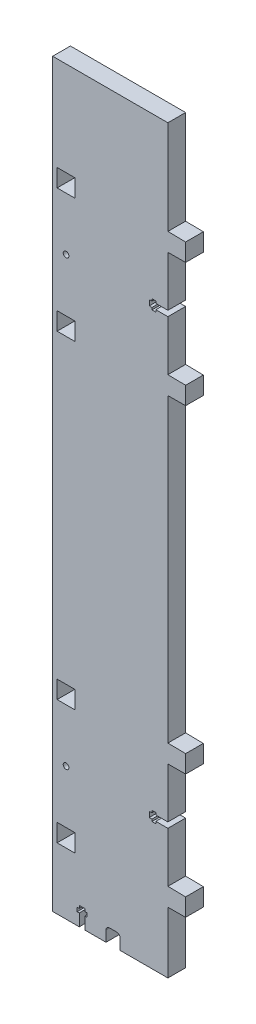
SolidWorks part; units mm, degrees
ref_plane "Front" through (0, 0, 0) normal (0, 0, 1) x (1, 0, 0)
ref_plane "Top" through (0, 0, 0) normal (0, 1, 0) x (1, 0, 0)
ref_plane "Right" through (0, 0, 0) normal (1, 0, 0) x (0, 0, -1)
sketch "Эскиз1" plane through (0, 0, 0) normal (0, 0, 1) x (1, 0, 0)
  line L0 (-37.4993, -208.9512) -> (-37.4993, 208.9512)
  line L1 (-37.4993, 208.9512) -> (27.5007, 208.9512)
  line L2 (-34.9993, 145.8512) -> (-24.8993, 145.8512)
  line L3 (-24.8993, 145.8512) -> (-24.8993, 155.8512)
  line L4 (-24.8993, 155.8512) -> (-34.9993, 155.8512)
  line L5 (-34.9993, 155.8512) -> (-34.9993, 145.8512)
  line L6 (-34.9993, -174.1488) -> (-24.8993, -174.1488)
  line L7 (-24.8993, -174.1488) -> (-24.8993, -164.1488)
  line L8 (-24.8993, -164.1488) -> (-34.9993, -164.1488)
  line L9 (-34.9993, -164.1488) -> (-34.9993, -174.1488)
  line L10 (-34.9993, 75.8512) -> (-24.8993, 75.8512)
  line L11 (-24.8993, 75.8512) -> (-24.8993, 85.8512)
  line L12 (-24.8993, 85.8512) -> (-34.9993, 85.8512)
  line L13 (-34.9993, 85.8512) -> (-34.9993, 75.8512)
  line L14 (-34.9993, -104.1488) -> (-24.8993, -104.1488)
  line L15 (-24.8993, -104.1488) -> (-24.8993, -94.1488)
  line L16 (-24.8993, -94.1488) -> (-34.9993, -94.1488)
  line L17 (-34.9993, -94.1488) -> (-34.9993, -104.1488)
  line L18 (37.4993, 155.6845) -> (27.5007, 155.8512)
  line L19 (37.4993, 145.6845) -> (37.4993, 155.6845)
  line L20 (27.5007, 145.6512) -> (37.4993, 145.6845)
  line L21 (27.5007, 117.3012) -> (27.5007, 145.6512)
  line L22 (20.7007, 117.3012) -> (27.5007, 117.3012)
  line L23 (20.7007, 118.5012) -> (20.7007, 117.3012)
  line L24 (18.5007, 118.5012) -> (20.7007, 118.5012)
  line L25 (18.5007, 117.3012) -> (18.5007, 118.5012)
  line L26 (17.0007, 117.3012) -> (18.5007, 117.3012)
  line L27 (17.0007, 114.2012) -> (17.0007, 117.3012)
  line L28 (18.5007, 114.2012) -> (17.0007, 114.2012)
  line L29 (18.5007, 113.0012) -> (18.5007, 114.2012)
  line L30 (20.7007, 113.0012) -> (18.5007, 113.0012)
  line L31 (20.7007, 114.2012) -> (20.7007, 113.0012)
  line L32 (27.5007, 114.2012) -> (20.7007, 114.2012)
  line L33 (27.5007, 85.8512) -> (27.5007, 114.2012)
  line L34 (37.4993, 85.6845) -> (27.5007, 85.8512)
  line L35 (37.4993, 75.6845) -> (37.4993, 85.6845)
  line L36 (27.5007, 75.6512) -> (37.4993, 75.6845)
  line L37 (27.5007, -94.1488) -> (27.5007, 75.6512)
  line L38 (37.4993, -94.3155) -> (27.5007, -94.1488)
  line L39 (37.4993, -104.3155) -> (37.4993, -94.3155)
  line L40 (27.5007, -104.3488) -> (37.4993, -104.3155)
  line L41 (27.5007, -132.6988) -> (27.5007, -104.3488)
  line L42 (20.7007, -132.6988) -> (27.5007, -132.6988)
  line L43 (20.7007, -131.4988) -> (20.7007, -132.6988)
  line L44 (18.5007, -131.4988) -> (20.7007, -131.4988)
  line L45 (18.5007, -132.6988) -> (18.5007, -131.4988)
  line L46 (17.0007, -132.6988) -> (18.5007, -132.6988)
  line L47 (17.0007, -135.7988) -> (17.0007, -132.6988)
  line L48 (18.5007, -135.7988) -> (17.0007, -135.7988)
  line L49 (18.5007, -136.9988) -> (18.5007, -135.7988)
  line L50 (20.7007, -136.9988) -> (18.5007, -136.9988)
  line L51 (20.7007, -135.7988) -> (20.7007, -136.9988)
  line L52 (27.5007, -135.7988) -> (20.7007, -135.7988)
  line L53 (27.5007, -164.1488) -> (27.5007, -135.7988)
  line L54 (37.4993, -164.3155) -> (27.5007, -164.1488)
  line L55 (37.4993, -174.3155) -> (37.4993, -164.3155)
  line L56 (27.5007, -174.3488) -> (37.4993, -174.3155)
  line L57 (27.5007, 155.8512) -> (27.5007, 208.9512)
  line L58 (27.5007, -208.9512) -> (27.5007, -174.3488)
  line L59 (-19.3993, -202.1512) -> (-19.3993, -208.9512)
  line L60 (-18.1993, -202.1512) -> (-19.3993, -202.1512)
  line L61 (-18.1993, -199.9512) -> (-18.1993, -202.1512)
  line L62 (-19.3993, -199.9512) -> (-18.1993, -199.9512)
  line L63 (-19.3993, -198.4512) -> (-19.3993, -199.9512)
  line L64 (-22.4993, -198.4512) -> (-19.3993, -198.4512)
  line L65 (-22.4993, -199.9512) -> (-22.4993, -198.4512)
  line L66 (-23.6993, -199.9512) -> (-22.4993, -199.9512)
  line L67 (-23.6993, -202.1512) -> (-23.6993, -199.9512)
  line L68 (-22.4993, -202.1512) -> (-23.6993, -202.1512)
  line L69 (-22.4993, -208.9512) -> (-22.4993, -202.1512)
  line L70 (-37.4993, -208.9512) -> (-22.4993, -208.9512)
  line L71 (-19.3993, -208.9512) -> (-7.3993, -208.9512)
  line L72 (-7.3993, -208.9512) -> (-7.3993, -202.9512)
  line L73 (-5.3993, -200.9512) -> (-1.3993, -200.9512)
  line L74 (0.6007, -202.9512) -> (0.6007, -208.9512)
  line L75 (0.6007, -208.9512) -> (27.5007, -208.9512)
  circle A0 centre (-29.9493, 115.8512) radius 1.6
  circle A1 centre (-29.9493, -134.1488) radius 1.6
  arc A2 (-5.3993, -200.9512) -> (-7.3993, -202.9512) centre (-5.3993, -202.9512) ccw
  arc A3 (0.6007, -202.9512) -> (-1.3993, -200.9512) centre (-1.3993, -202.9512) ccw
extrude "Бобышка-Вытянуть1" add sketch "Эскиз1" along normal blind 10
